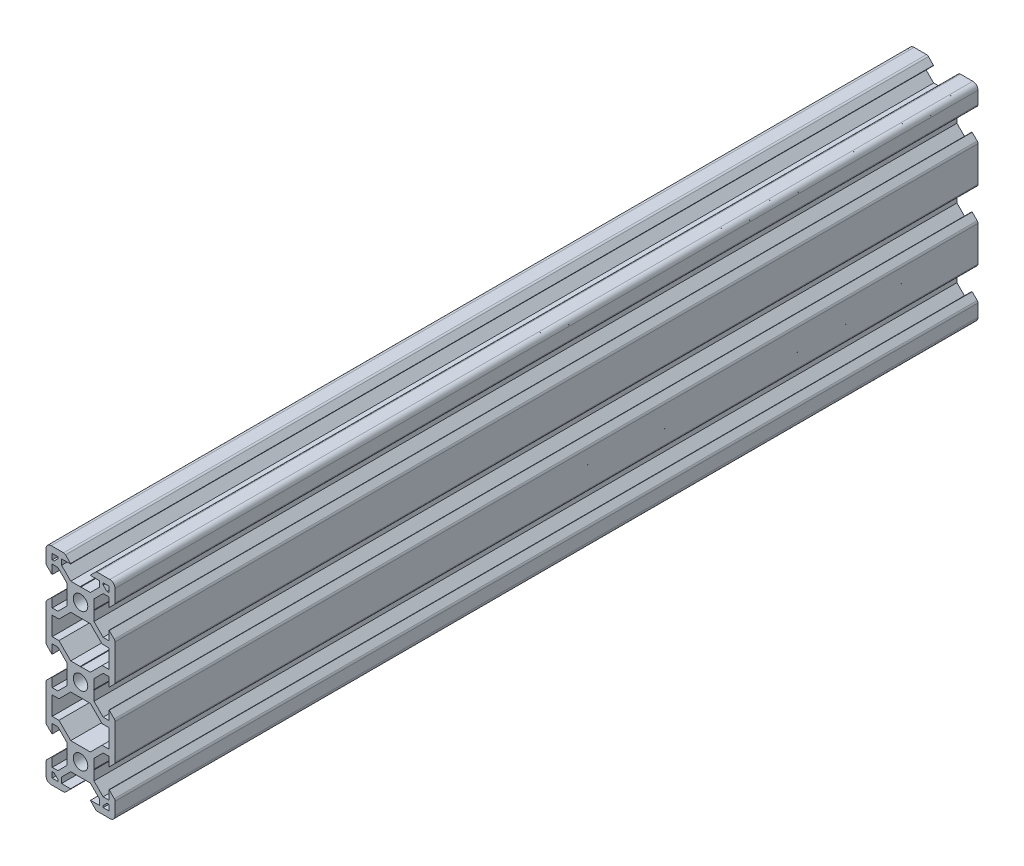
SolidWorks part; units mm, degrees
ref_plane "Front Plane" through (0, 0, 0) normal (0, 0, 1) x (1, 0, 0)
ref_plane "Top Plane" through (0, 0, 0) normal (0, 1, 0) x (1, 0, 0)
ref_plane "Right Plane" through (0, 0, 0) normal (1, 0, 0) x (0, 0, -1)
sketch "Sketch2" plane through (0, 0, 0) normal (0, 0, 1) x (1, 0, 0)
  line L0 (-8.2, 2.8875) -> (-8.2, 5.4975)
  line L3 (-4.9072, 9.9975) -> (-8.5, 9.9975)
  line L4 (-10, 4.9047) -> (-10, 8.4975)
  line L5 (-2.1, 0) -> (-3.8, 0) construction
  line L6 (0, 3.8) -> (0, 2.1) construction
  line L7 (-0.1, 3.9) -> (-2.8404, 3.9)
  line L8 (-3.9, 0.1) -> (-3.9, 2.8383)
  line L9 (-2.89, 8.1975) -> (-5.5, 8.1975)
  line L10 (-6.57, 8.1975) -> (-6.57, 7.6575)
  line L11 (-8.2, 6.5675) -> (-7.66, 6.5675)
  line L12 (-5.5, 8.1975) -> (-5.5, 6.5588)
  line L13 (-6.56, 5.4975) -> (-8.2, 5.4975)
  line L14 (-8.2, 8.1975) -> (-1.4852, 1.4847) construction
  line L15 (-6.56, 5.4975) -> (-3.9, 2.8383)
  line L16 (-5.5, 6.5588) -> (-2.8404, 3.9)
  line L17 (-7.66, 6.5675) -> (-6.57, 7.6575)
  line L18 (-8.7302, 7.6671) -> (-0.5302, -0.5304) construction
  line L19 (-7.6698, 8.7279) -> (0.5302, 0.5304) construction
  line L20 (-8.2, 8.1975) -> (0, 0) construction
  line L21 (-8.2, 6.5675) -> (-8.2, 8.1975)
  line L22 (-8.2, -0.0025) -> (-8.2, 8.1975) construction
  line L23 (-6.57, 8.1975) -> (-8.2, 8.1975)
  line L24 (0, 8.1975) -> (-8.2, 8.1975) construction
  line L25 (-10, -0.0025) -> (-10, 9.9975) construction
  line L26 (0, 9.9975) -> (-10, 9.9975) construction
  line L27 (-2.89, 8.3075) -> (-2.89, 8.1975)
  line L29 (-8.31, 2.8875) -> (-8.2, 2.8875)
  line L30 (-4.3486, 9.7661) -> (-2.89, 8.3075)
  line L31 (-8.31, 2.8875) -> (-9.7686, 4.3461)
  line L34 (-0.1, 3.9) -> (0, 3.8)
  line L35 (-3.9, 0.1) -> (-3.8, 0)
  line L36 (-10, -20) -> (0, -20) construction
  line L37 (0, 0) -> (0, -20) construction
  line L38 (0, -3.9) -> (-2.8404, -3.9)
  line L39 (-3.8, 0) -> (-3.9, -0.1)
  line L40 (-3.9, -0.1) -> (-3.9, -2.84)
  line L41 (-2.8404, -3.9) -> (-6.25, -7.3096)
  line L42 (-3.9, -2.84) -> (-6.56, -5.5)
  line L43 (-8.21, -2.89) -> (-8.21, -5.5)
  line L44 (-6.56, 5.4975) -> (-6.56, -5.5) construction
  line L45 (-6.56, -5.5) -> (-8.21, -5.5)
  line L46 (-6.25, -7.3096) -> (-6.25, -12.7) construction
  line L47 (-6.25, -7.3096) -> (-8.21, -7.3096)
  line L48 (-8.21, -2.89) -> (-8.31, -2.89)
  line L49 (-8.31, -2.89) -> (-9.7657, -4.3457)
  line L51 (-8.21, -7.3096) -> (-8.21, -12.7)
  line L52 (-0.1, -16.1) -> (-2.85, -16.1)
  line L53 (-3.9, -17.16) -> (-3.9, -19.9)
  line L54 (-6.25, -12.7) -> (-2.85, -16.1)
  line L58 (-3.9, -17.16) -> (-6.56, -14.5)
  line L60 (-8.21, -17.11) -> (-8.31, -17.11)
  line L61 (-10, -4.9114) -> (-10, -15.0886)
  line L62 (-9.7657, -15.6543) -> (-8.31, -17.11)
  line L63 (-0.1, -16.1) -> (0, -16.2)
  line L64 (-3.9, -19.9) -> (-3.8, -20)
  line L65 (-8.21, -14.5) -> (-6.56, -14.5)
  line L66 (-8.21, -12.7) -> (-6.25, -12.7)
  line L68 (-8.21, -14.5) -> (-8.21, -17.11)
  arc A1 (-10, 8.4975) -> (-8.5, 9.9975) centre (-8.5, 8.4975) cw
  arc A2 (-9.7686, 4.3461) -> (-10, 4.9047) centre (-9.21, 4.9047) cw
  arc A3 (-4.3486, 9.7661) -> (-4.9072, 9.9975) centre (-4.9072, 9.2075) ccw
  arc A4 (-2.1, -20) -> (0, -17.9) centre (0, -20) cw
  arc A5 (0, 2.1) -> (0, -2.1) centre (0, 0) ccw
  arc A6 (-9.7657, -15.6543) -> (-10, -15.0886) centre (-9.2, -15.0886) cw
  arc A7 (-9.7657, -4.3457) -> (-10, -4.9114) centre (-9.2, -4.9114) ccw
  point P29 (-10, 9.9975)
  point P39 (-10, 4.5775)
  point P42 (-4.58, 9.9975)
  point P76 (-10, -15.42)
  point P79 (-10, -4.58)
  dimension "D15" = 1.5
  dimension "D22" = 0.79
  dimension "D30" = 2.1
  dimension "D31" = 2.1
  dimension "D51" = 0.8
  dimension "D4" = 1.8
  dimension "D5" = 3.43
  dimension "D6" = 3.43
  dimension "D7" = 0.54
  dimension "D8" = 0.54
  dimension "D9" = 1.07
  dimension "D10" = 1.07
  dimension "D11" = 3.9
  dimension "D12" = 3.9
  dimension "D16" = 7.11
  dimension "D17" = 0.11
  dimension "D18" = 1.69
  dimension "D19" = 0.11
  dimension "D20" = 7.11
  dimension "D21" = 1.69
  dimension "D23" = 10
  dimension "D24" = 0.1
  dimension "D25" = 45
  dimension "D26" = 0.1
  dimension "D27" = 45
  dimension "D28" = 1.64
  dimension "D29" = 20
  dimension "D32" = 3.9
  dimension "D33" = 45
  dimension "D34" = 2.74
  dimension "D35" = 45
  dimension "D36" = 1.96
  dimension "D37" = 2.61
  dimension "D38" = 90
  dimension "D39" = 2.61
  dimension "D40" = 3.9
  dimension "D41" = 3.9
  dimension "D42" = 135
  dimension "D44" = 45
  dimension "D45" = 1.8
  dimension "D46" = 0.1
  dimension "D47" = 0.1
  dimension "D48" = 45
  dimension "D49" = 0.1
  dimension "D50" = 45
  dimension "D43" = 5.5
  dimension "D13" = 0.75
  dimension "D14" = 0.75
sketch "Sketch6" plane through (0, 0, 0) normal (0, 0, 1) x (1, 0, 0)
  line L0 (-0.1, 3.9) -> (0, 3.8) construction
  line L1 (-0.1, 3.9) -> (-2.8404, 3.9) construction
  line L2 (-5.5, 6.5588) -> (-2.8404, 3.9) construction
  line L3 (-5.5, 8.1975) -> (-5.5, 6.5588) construction
  line L4 (-2.89, 8.1975) -> (-5.5, 8.1975) construction
  line L5 (-7.66, 6.5675) -> (-6.57, 7.6575)
  line L6 (-6.57, 7.6575) -> (-6.57, 8.1975)
  line L7 (-6.57, 8.1975) -> (-8.2, 8.1975)
  line L8 (-8.2, 8.1975) -> (-8.2, 6.5675)
  line L9 (-8.2, 6.5675) -> (-7.66, 6.5675)
  line L10 (-7.66, 6.5675) -> (-6.57, 7.6575)
  line L11 (-6.57, 7.6575) -> (-6.57, 8.1975)
  line L12 (-6.57, 8.1975) -> (-8.2, 8.1975)
  line L13 (-8.2, 8.1975) -> (-8.2, 6.5675)
  line L14 (-8.2, 6.5675) -> (-7.66, 6.5675)
  line L15 (-2.89, 8.3075) -> (-2.89, 8.1975) construction
  line L16 (-4.3486, 9.7661) -> (-2.89, 8.3075) construction
  line L17 (-4.9072, 9.9975) -> (-8.5, 9.9975) construction
  line L18 (-10, 4.9047) -> (-10, 8.4975) construction
  line L19 (-8.31, 2.8875) -> (-9.7686, 4.3461) construction
  line L20 (-8.31, 2.8875) -> (-8.2, 2.8875) construction
  line L21 (-8.2, 2.8875) -> (-8.2, 5.4975) construction
  line L22 (-6.56, 5.4975) -> (-8.2, 5.4975) construction
  line L23 (-6.56, 5.4975) -> (-3.9, 2.8383) construction
  line L24 (-3.9, 0.1) -> (-3.9, 2.8383) construction
  line L25 (-3.9, 0.1) -> (-3.8, 0) construction
  line L26 (-3.8, 0) -> (-3.9, -0.1) construction
  line L27 (-3.9, -0.1) -> (-3.9, -2.84) construction
  line L28 (-3.9, -2.84) -> (-6.56, -5.5) construction
  line L29 (-6.56, -5.5) -> (-8.21, -5.5) construction
  line L30 (-8.21, -2.89) -> (-8.21, -5.5) construction
  line L31 (-8.21, -2.89) -> (-8.31, -2.89) construction
  line L32 (-8.31, -2.89) -> (-9.7657, -4.3457) construction
  line L33 (-10, -4.9114) -> (-10, -15.0886) construction
  line L34 (-9.7657, -15.6543) -> (-8.31, -17.11) construction
  line L35 (-8.21, -17.11) -> (-8.31, -17.11) construction
  line L36 (-8.21, -14.5) -> (-8.21, -17.11) construction
  line L37 (-8.21, -14.5) -> (-6.56, -14.5) construction
  line L38 (-3.9, -17.16) -> (-6.56, -14.5) construction
  line L39 (-3.9, -17.16) -> (-3.9, -19.9) construction
  line L40 (-3.9, -19.9) -> (-3.8, -20) construction
  line L41 (0, -3.9) -> (-2.8404, -3.9) construction
  line L42 (-2.8404, -3.9) -> (-6.25, -7.3096) construction
  line L43 (-6.25, -7.3096) -> (-8.21, -7.3096) construction
  line L44 (-8.21, -7.3096) -> (-8.21, -12.7) construction
  line L45 (-8.21, -12.7) -> (-6.25, -12.7) construction
  line L46 (-6.25, -12.7) -> (-2.85, -16.1) construction
  line L47 (-0.1, -16.1) -> (-2.85, -16.1) construction
  line L48 (-0.1, -16.1) -> (0, -16.2) construction
  line L49 (-0.1, 3.9) -> (0, 3.8)
  line L50 (-0.1, 3.9) -> (-2.8404, 3.9)
  line L51 (-5.5, 6.5588) -> (-2.8404, 3.9)
  line L52 (-5.5, 8.1975) -> (-5.5, 6.5588)
  line L53 (-2.89, 8.1975) -> (-5.5, 8.1975)
  line L54 (-2.89, 8.3075) -> (-2.89, 8.1975)
  line L55 (-4.3486, 9.7661) -> (-2.89, 8.3075)
  line L56 (-4.9072, 9.9975) -> (-8.5, 9.9975)
  line L57 (-10, 4.9047) -> (-10, 8.4975)
  line L58 (-8.31, 2.8875) -> (-9.7686, 4.3461)
  line L59 (-8.31, 2.8875) -> (-8.2, 2.8875)
  line L60 (-8.2, 2.8875) -> (-8.2, 5.4975)
  line L61 (-6.56, 5.4975) -> (-8.2, 5.4975)
  line L62 (-6.56, 5.4975) -> (-3.9, 2.8383)
  line L63 (-3.9, 0.1) -> (-3.9, 2.8383)
  line L64 (-3.9, 0.1) -> (-3.8, 0)
  line L65 (-3.8, 0) -> (-3.9, -0.1)
  line L66 (-3.9, -0.1) -> (-3.9, -2.84)
  line L67 (-3.9, -2.84) -> (-6.56, -5.5)
  line L68 (-6.56, -5.5) -> (-8.21, -5.5)
  line L69 (-8.21, -2.89) -> (-8.21, -5.5)
  line L70 (-8.21, -2.89) -> (-8.31, -2.89)
  line L71 (-8.31, -2.89) -> (-9.7657, -4.3457)
  line L72 (-10, -4.9114) -> (-10, -15.0886)
  line L73 (-9.7657, -15.6543) -> (-8.31, -17.11)
  line L74 (-8.21, -17.11) -> (-8.31, -17.11)
  line L75 (-8.21, -14.5) -> (-8.21, -17.11)
  line L76 (-8.21, -14.5) -> (-6.56, -14.5)
  line L77 (-3.9, -17.16) -> (-6.56, -14.5)
  line L78 (-3.9, -17.16) -> (-3.9, -19.9)
  line L79 (-3.9, -19.9) -> (-3.8, -20)
  line L80 (2.8404, -3.9) -> (-2.8404, -3.9)
  line L81 (-2.8404, -3.9) -> (-6.25, -7.3096)
  line L82 (-6.25, -7.3096) -> (-8.21, -7.3096)
  line L83 (-8.21, -7.3096) -> (-8.21, -12.7)
  line L84 (-8.21, -12.7) -> (-6.25, -12.7)
  line L85 (-6.25, -12.7) -> (-2.85, -16.1)
  line L86 (-0.1, -16.1) -> (-2.85, -16.1)
  line L87 (-0.1, -16.1) -> (0, -16.2)
  line L88 (0, 9.9975) -> (0, -49.9975) construction
  line L89 (-10, -20) -> (10, -20) construction
  line L90 (0.1, -16.1) -> (0, -16.2)
  line L91 (0.1, -16.1) -> (2.85, -16.1)
  line L92 (6.25, -12.7) -> (2.85, -16.1)
  line L93 (8.21, -12.7) -> (6.25, -12.7)
  line L94 (8.21, -7.3096) -> (8.21, -12.7)
  line L95 (6.25, -7.3096) -> (8.21, -7.3096)
  line L96 (2.8404, -3.9) -> (6.25, -7.3096)
  line L97 (3.9, -19.9) -> (3.8, -20)
  line L98 (3.9, -17.16) -> (3.9, -19.9)
  line L99 (3.9, -17.16) -> (6.56, -14.5)
  line L100 (8.21, -14.5) -> (6.56, -14.5)
  line L101 (8.21, -14.5) -> (8.21, -17.11)
  line L102 (8.21, -17.11) -> (8.31, -17.11)
  line L103 (9.7657, -15.6543) -> (8.31, -17.11)
  line L104 (10, -4.9114) -> (10, -15.0886)
  line L105 (8.31, -2.89) -> (9.7657, -4.3457)
  line L106 (8.21, -2.89) -> (8.31, -2.89)
  line L107 (8.21, -2.89) -> (8.21, -5.5)
  line L108 (6.56, -5.5) -> (8.21, -5.5)
  line L109 (3.9, -2.84) -> (6.56, -5.5)
  line L110 (3.9, -0.1) -> (3.9, -2.84)
  line L111 (3.8, 0) -> (3.9, -0.1)
  line L112 (3.9, 0.1) -> (3.8, 0)
  line L113 (3.9, 0.1) -> (3.9, 2.8383)
  line L114 (6.56, 5.4975) -> (3.9, 2.8383)
  line L115 (6.56, 5.4975) -> (8.2, 5.4975)
  line L116 (8.2, 2.8875) -> (8.2, 5.4975)
  line L117 (8.31, 2.8875) -> (8.2, 2.8875)
  line L118 (8.31, 2.8875) -> (9.7686, 4.3461)
  line L119 (10, 4.9047) -> (10, 8.4975)
  line L120 (4.9072, 9.9975) -> (8.5, 9.9975)
  line L121 (4.3486, 9.7661) -> (2.89, 8.3075)
  line L122 (2.89, 8.3075) -> (2.89, 8.1975)
  line L123 (2.89, 8.1975) -> (5.5, 8.1975)
  line L124 (5.5, 8.1975) -> (5.5, 6.5588)
  line L125 (5.5, 6.5588) -> (2.8404, 3.9)
  line L126 (0.1, 3.9) -> (2.8404, 3.9)
  line L127 (0.1, 3.9) -> (0, 3.8)
  line L128 (8.2, 6.5675) -> (7.66, 6.5675)
  line L129 (8.2, 8.1975) -> (8.2, 6.5675)
  line L130 (6.57, 8.1975) -> (8.2, 8.1975)
  line L131 (6.57, 7.6575) -> (6.57, 8.1975)
  line L132 (7.66, 6.5675) -> (6.57, 7.6575)
  line L133 (7.66, -46.5675) -> (6.57, -47.6575)
  line L134 (6.57, -47.6575) -> (6.57, -48.1975)
  line L135 (6.57, -48.1975) -> (8.2, -48.1975)
  line L136 (8.2, -48.1975) -> (8.2, -46.5675)
  line L137 (8.2, -46.5675) -> (7.66, -46.5675)
  line L138 (0.1, -43.9) -> (0, -43.8)
  line L139 (0.1, -43.9) -> (2.8404, -43.9)
  line L140 (5.5, -46.5588) -> (2.8404, -43.9)
  line L141 (5.5, -48.1975) -> (5.5, -46.5588)
  line L142 (2.89, -48.1975) -> (5.5, -48.1975)
  line L143 (2.89, -48.3075) -> (2.89, -48.1975)
  line L144 (4.3486, -49.7661) -> (2.89, -48.3075)
  line L145 (4.9072, -49.9975) -> (8.5, -49.9975)
  line L146 (10, -44.9047) -> (10, -48.4975)
  line L147 (8.31, -42.8875) -> (9.7686, -44.3461)
  line L148 (8.31, -42.8875) -> (8.2, -42.8875)
  line L149 (8.2, -42.8875) -> (8.2, -45.4975)
  line L150 (6.56, -45.4975) -> (8.2, -45.4975)
  line L151 (6.56, -45.4975) -> (3.9, -42.8383)
  line L152 (3.9, -40.1) -> (3.9, -42.8383)
  line L153 (3.9, -40.1) -> (3.8, -40)
  line L154 (3.8, -40) -> (3.9, -39.9)
  line L155 (3.9, -39.9) -> (3.9, -37.16)
  line L156 (3.9, -37.16) -> (6.56, -34.5)
  line L157 (6.56, -34.5) -> (8.21, -34.5)
  line L158 (8.21, -37.11) -> (8.21, -34.5)
  line L159 (8.21, -37.11) -> (8.31, -37.11)
  line L160 (8.31, -37.11) -> (9.7657, -35.6543)
  line L161 (10, -35.0886) -> (10, -24.9114)
  line L162 (9.7657, -24.3457) -> (8.31, -22.89)
  line L163 (8.21, -22.89) -> (8.31, -22.89)
  line L164 (8.21, -25.5) -> (8.21, -22.89)
  line L165 (8.21, -25.5) -> (6.56, -25.5)
  line L166 (3.9, -22.84) -> (6.56, -25.5)
  line L167 (3.9, -22.84) -> (3.9, -20.1)
  line L168 (3.9, -20.1) -> (3.8, -20)
  line L169 (2.8404, -36.1) -> (6.25, -32.6904)
  line L170 (6.25, -32.6904) -> (8.21, -32.6904)
  line L171 (8.21, -32.6904) -> (8.21, -27.3)
  line L172 (8.21, -27.3) -> (6.25, -27.3)
  line L173 (6.25, -27.3) -> (2.85, -23.9)
  line L174 (0.1, -23.9) -> (2.85, -23.9)
  line L175 (0.1, -23.9) -> (0, -23.8)
  line L176 (-0.1, -23.9) -> (0, -23.8)
  line L177 (-0.1, -23.9) -> (-2.85, -23.9)
  line L178 (-6.25, -27.3) -> (-2.85, -23.9)
  line L179 (-8.21, -27.3) -> (-6.25, -27.3)
  line L180 (-8.21, -32.6904) -> (-8.21, -27.3)
  line L181 (-6.25, -32.6904) -> (-8.21, -32.6904)
  line L182 (-2.8404, -36.1) -> (-6.25, -32.6904)
  line L183 (2.8404, -36.1) -> (-2.8404, -36.1)
  line L184 (-3.9, -20.1) -> (-3.8, -20)
  line L185 (-3.9, -22.84) -> (-3.9, -20.1)
  line L186 (-3.9, -22.84) -> (-6.56, -25.5)
  line L187 (-8.21, -25.5) -> (-6.56, -25.5)
  line L188 (-8.21, -25.5) -> (-8.21, -22.89)
  line L189 (-8.21, -22.89) -> (-8.31, -22.89)
  line L190 (-9.7657, -24.3457) -> (-8.31, -22.89)
  line L191 (-10, -35.0886) -> (-10, -24.9114)
  line L192 (-8.31, -37.11) -> (-9.7657, -35.6543)
  line L193 (-8.21, -37.11) -> (-8.31, -37.11)
  line L194 (-8.21, -37.11) -> (-8.21, -34.5)
  line L195 (-6.56, -34.5) -> (-8.21, -34.5)
  line L196 (-3.9, -37.16) -> (-6.56, -34.5)
  line L197 (-3.9, -39.9) -> (-3.9, -37.16)
  line L198 (-3.8, -40) -> (-3.9, -39.9)
  line L199 (-3.9, -40.1) -> (-3.8, -40)
  line L200 (-3.9, -40.1) -> (-3.9, -42.8383)
  line L201 (-6.56, -45.4975) -> (-3.9, -42.8383)
  line L202 (-6.56, -45.4975) -> (-8.2, -45.4975)
  line L203 (-8.2, -42.8875) -> (-8.2, -45.4975)
  line L204 (-8.31, -42.8875) -> (-8.2, -42.8875)
  line L205 (-8.31, -42.8875) -> (-9.7686, -44.3461)
  line L206 (-10, -44.9047) -> (-10, -48.4975)
  line L207 (-4.9072, -49.9975) -> (-8.5, -49.9975)
  line L208 (-4.3486, -49.7661) -> (-2.89, -48.3075)
  line L209 (-2.89, -48.3075) -> (-2.89, -48.1975)
  line L210 (-2.89, -48.1975) -> (-5.5, -48.1975)
  line L211 (-5.5, -48.1975) -> (-5.5, -46.5588)
  line L212 (-5.5, -46.5588) -> (-2.8404, -43.9)
  line L213 (-0.1, -43.9) -> (-2.8404, -43.9)
  line L214 (-0.1, -43.9) -> (0, -43.8)
  line L215 (-8.2, -46.5675) -> (-7.66, -46.5675)
  line L216 (-8.2, -48.1975) -> (-8.2, -46.5675)
  line L217 (-6.57, -48.1975) -> (-8.2, -48.1975)
  line L218 (-6.57, -47.6575) -> (-6.57, -48.1975)
  line L219 (-7.66, -46.5675) -> (-6.57, -47.6575)
  arc A0 (0, 2.1) -> (0, -2.1) centre (0, 0) ccw construction
  arc A1 (0, -17.9) -> (-2.1, -20) centre (0, -20) ccw construction
  arc A2 (-4.3486, 9.7661) -> (-4.9072, 9.9975) centre (-4.9072, 9.2075) ccw construction
  arc A3 (-8.5, 9.9975) -> (-10, 8.4975) centre (-8.5, 8.4975) ccw construction
  arc A4 (-10, 4.9047) -> (-9.7686, 4.3461) centre (-9.21, 4.9047) ccw construction
  arc A5 (-9.7657, -4.3457) -> (-10, -4.9114) centre (-9.2, -4.9114) ccw construction
  arc A6 (-10, -15.0886) -> (-9.7657, -15.6543) centre (-9.2, -15.0886) ccw construction
  circle A7 centre (0, 0) radius 2.1
  circle A8 centre (0, -20) radius 2.1
  arc A9 (-4.3486, 9.7661) -> (-4.9072, 9.9975) centre (-4.9072, 9.2075) ccw
  arc A10 (-8.5, 9.9975) -> (-10, 8.4975) centre (-8.5, 8.4975) ccw
  arc A11 (-10, 4.9047) -> (-9.7686, 4.3461) centre (-9.21, 4.9047) ccw
  arc A12 (-9.7657, -4.3457) -> (-10, -4.9114) centre (-9.2, -4.9114) ccw
  arc A13 (-10, -15.0886) -> (-9.7657, -15.6543) centre (-9.2, -15.0886) ccw
  arc A14 (10, -15.0886) -> (9.7657, -15.6543) centre (9.2, -15.0886) cw
  arc A15 (9.7657, -4.3457) -> (10, -4.9114) centre (9.2, -4.9114) cw
  arc A16 (10, 4.9047) -> (9.7686, 4.3461) centre (9.21, 4.9047) cw
  arc A17 (8.5, 9.9975) -> (10, 8.4975) centre (8.5, 8.4975) cw
  arc A18 (4.3486, 9.7661) -> (4.9072, 9.9975) centre (4.9072, 9.2075) cw
  arc A19 (4.3486, -49.7661) -> (4.9072, -49.9975) centre (4.9072, -49.2075) ccw
  arc A20 (8.5, -49.9975) -> (10, -48.4975) centre (8.5, -48.4975) ccw
  arc A21 (10, -44.9047) -> (9.7686, -44.3461) centre (9.21, -44.9047) ccw
  arc A22 (9.7657, -35.6543) -> (10, -35.0886) centre (9.2, -35.0886) ccw
  arc A23 (10, -24.9114) -> (9.7657, -24.3457) centre (9.2, -24.9114) ccw
  arc A24 (-10, -24.9114) -> (-9.7657, -24.3457) centre (-9.2, -24.9114) cw
  arc A25 (-9.7657, -35.6543) -> (-10, -35.0886) centre (-9.2, -35.0886) cw
  arc A26 (-10, -44.9047) -> (-9.7686, -44.3461) centre (-9.21, -44.9047) cw
  arc A27 (-8.5, -49.9975) -> (-10, -48.4975) centre (-8.5, -48.4975) cw
  arc A28 (-4.3486, -49.7661) -> (-4.9072, -49.9975) centre (-4.9072, -49.2075) cw
  circle A29 centre (0, -40) radius 2.1
  dimension "D1" = 0
extrude "Boss-Extrude1" add sketch "Sketch6" against normal blind 250
